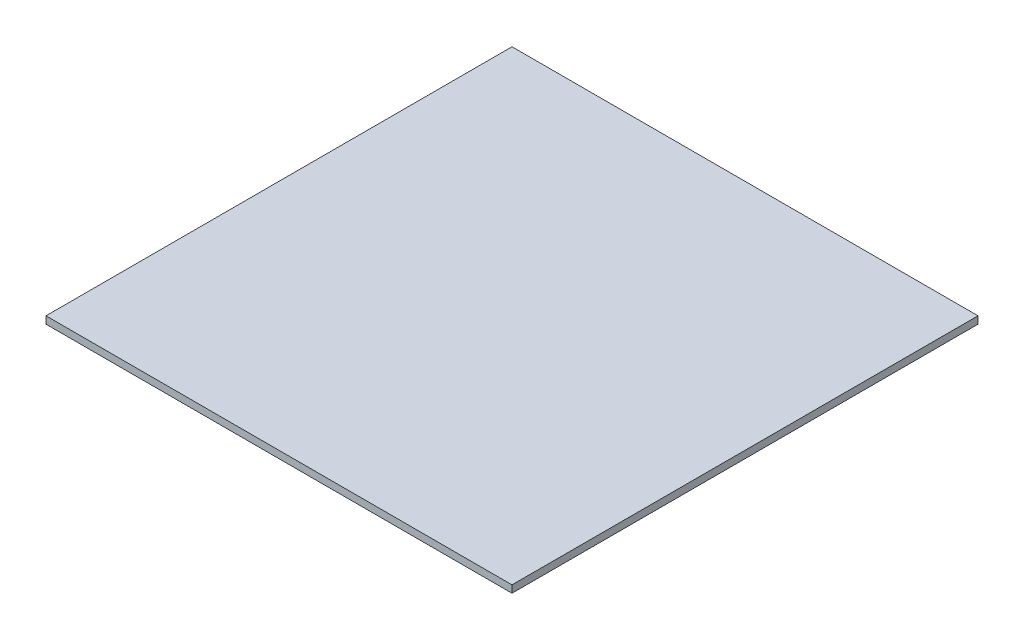
SolidWorks part; units mm, degrees
ref_plane "Front Plane" through (0, 0, 0) normal (0, 0, 1) x (1, 0, 0)
ref_plane "Top Plane" through (0, 0, 0) normal (0, 1, 0) x (1, 0, 0)
ref_plane "Right Plane" through (0, 0, 0) normal (1, 0, 0) x (0, 0, -1)
sketch "Sketch1" plane through (0, 0, 0) normal (0, 1, 0) x (1, 0, 0)
  line L1 (-304.8, -304.8) -> (304.8, -304.8)
  line L2 (-304.8, -304.8) -> (-304.8, 304.8)
  line L3 (-304.8, 304.8) -> (304.8, 304.8)
  line L4 (304.8, -304.8) -> (304.8, 304.8)
  line L5 (-304.8, -304.8) -> (304.8, 304.8) construction
  line L6 (-304.8, 304.8) -> (304.8, -304.8) construction
  point P0 (0, 0)
  dimension "D1" = 609.6
  dimension "D2" = 609.6
extrude "Boss-Extrude1" add sketch "Sketch1" along normal blind 9.525
